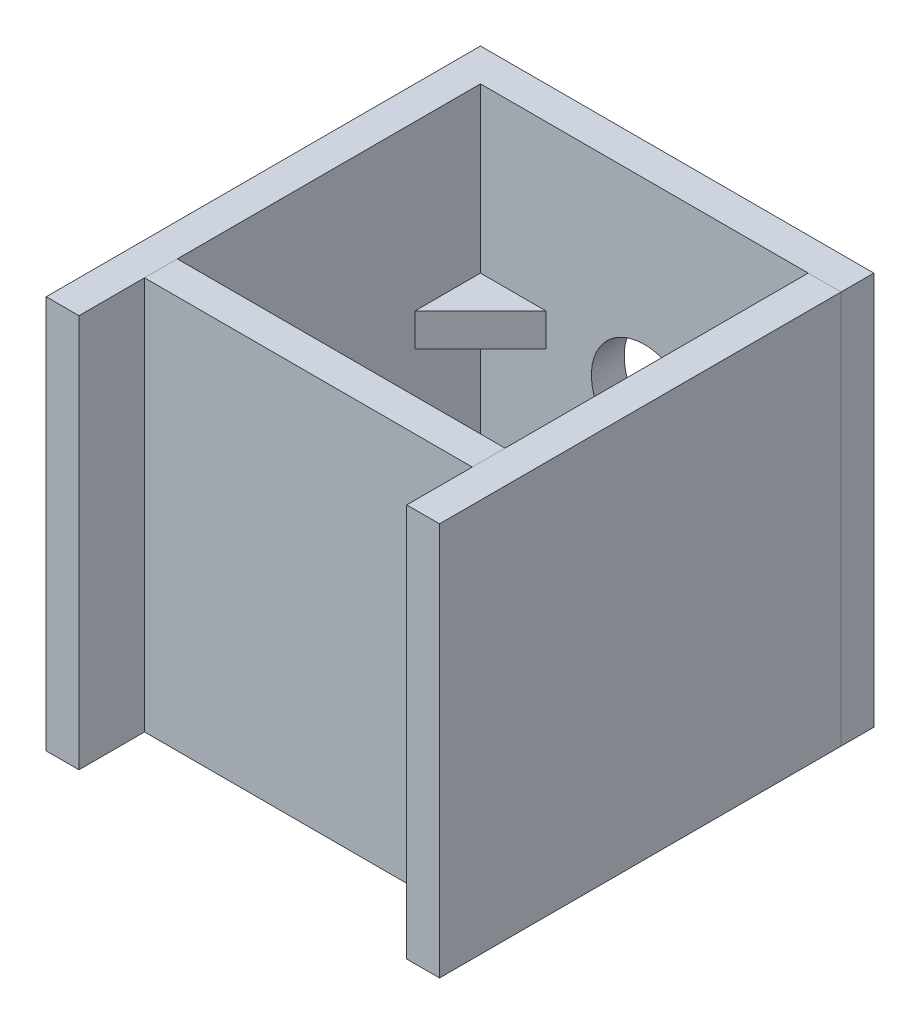
SolidWorks part; units mm, degrees
ref_plane "Front Plane" through (0, 0, 0) normal (0, 0, 1) x (1, 0, 0)
ref_plane "Top Plane" through (0, 0, 0) normal (0, 1, 0) x (1, 0, 0)
ref_plane "Right Plane" through (0, 0, 0) normal (1, 0, 0) x (0, 0, -1)
sketch "Sketch1" plane through (0, 0, 0) normal (0, 0, 1) x (1, 0, 0)
  line L1 (38.1, -38.1) -> (-38.1, -38.1)
  line L2 (38.1, -38.1) -> (38.1, 38.1)
  line L3 (38.1, 38.1) -> (-38.1, 38.1)
  line L4 (-38.1, -38.1) -> (-38.1, 38.1)
  line L5 (38.1, -38.1) -> (-38.1, 38.1) construction
  line L6 (38.1, 38.1) -> (-38.1, -38.1) construction
  point P0 (0, 0)
  dimension "D1" = 76.2
extrude "Boss-Extrude1" add sketch "Sketch1" along normal blind 6.35
sketch "Sketch2" plane through (0, 0, 6.35) normal (0, 0, 1) x (1, 0, 0)
  line L0 (-38.1, -38.1) -> (38.1, -38.1) construction
  line L1 (-38.1, 38.1) -> (-31.75, 38.1)
  line L2 (-38.1, 38.1) -> (-38.1, -38.1)
  line L3 (-38.1, -38.1) -> (-31.75, -38.1)
  line L4 (-31.75, 38.1) -> (-31.75, -38.1)
  line L6 (38.1, 38.1) -> (31.75, 38.1)
  line L7 (38.1, 38.1) -> (38.1, -38.1)
  line L8 (38.1, -38.1) -> (31.75, -38.1)
  line L9 (31.75, 38.1) -> (31.75, -38.1)
  dimension "D1" = 6.35
extrude "Boss-Extrude2" add sketch "Sketch2" along normal blind 77.7875 separate body
sketch "Sketch3" plane through (0, 0, 6.35) normal (0, 0, 1) x (1, 0, 0)
  line L0 (-38.1, -38.1) -> (38.1, -38.1) construction
  circle A0 centre (0, 0) radius 10.2616
  dimension "D1" = 20.5232
extrude "Cut-Extrude1" cut sketch "Sketch3" against normal through all
sketch "Sketch4" plane through (0, 0, 0) normal (0, 1, 0) x (1, 0, 0)
  line L0 (-31.75, -84.1375) -> (-31.75, -6.35) construction
  line L1 (-31.75, -65.0875) -> (31.75, -65.0875)
  line L2 (-31.75, -65.0875) -> (-31.75, -71.4375)
  line L3 (-31.75, -71.4375) -> (31.75, -71.4375)
  line L4 (31.75, -65.0875) -> (31.75, -71.4375)
  line L5 (31.75, -84.1375) -> (31.75, -6.35) construction
  line L7 (-31.75, -84.1375) -> (-38.1, -84.1375) construction
  dimension "D1" = 12.7
  dimension "D2" = 6.35
extrude "Boss-Extrude3" add sketch "Sketch4" along normal up to surface and the other way up to surface separate body up to face at (-34.925, 38.1, 45.2437) other way up to face at (-34.925, -38.1, 45.2437)
sketch "Sketch5" plane through (0, 0, 0) normal (0, 1, 0) x (1, 0, 0)
  line L0 (-19.05, -6.35) -> (-31.75, -19.05)
  line L1 (38.1, -6.35) -> (-38.1, -6.35) construction
  line L2 (-31.75, -84.1375) -> (-31.75, -6.35) construction
  line L3 (-31.75, -19.05) -> (-31.75, -6.35)
  line L4 (-31.75, -6.35) -> (-19.05, -6.35)
  dimension "D2" = 12.7
extrude "Boss-Extrude4" add sketch "Sketch5" along normal blind 6.35
